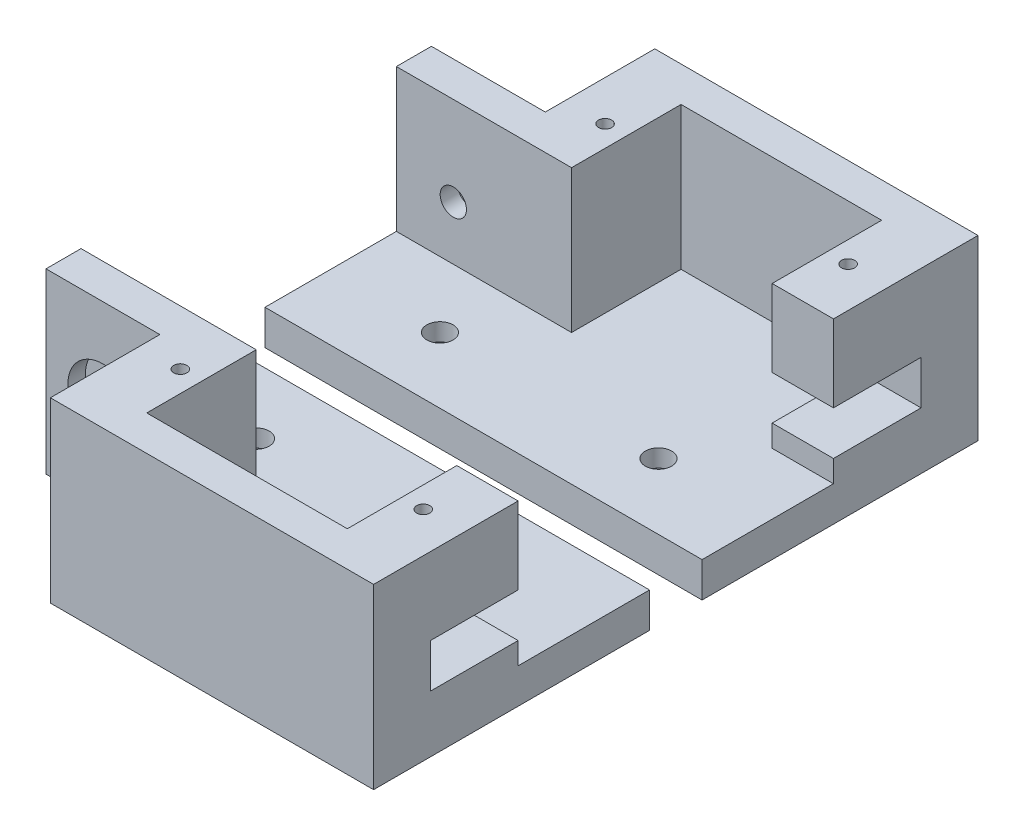
SolidWorks part; units mm, degrees
ref_plane "Front Plane" through (0, 0, 0) normal (0, 0, 1) x (1, 0, 0)
ref_plane "Top Plane" through (0, 0, 0) normal (0, 1, 0) x (1, 0, 0)
ref_plane "Right Plane" through (0, 0, 0) normal (1, 0, 0) x (0, 0, -1)
sketch "Sketch1" plane through (0, 0, 0) normal (0, 1, 0) x (1, 0, 0)
  line L0 (-20, 0) -> (0, 0)
  line L1 (0, 0) -> (0, 12.5)
  line L2 (0, 12.5) -> (22.9, 12.5)
  line L3 (22.9, 12.5) -> (22.9, 0)
  dimension "D1" = 22.9
  dimension "D2" = 12.5
  dimension "D3" = 20
extrude "Extrude-Thin1" add sketch "Sketch1" along normal blind 16.3 thin thin type one direction reverse wall 4
sketch "Sketch2" plane through (0, 0, 0) normal (0, -1, 0) x (1, 0, 0)
  line L2 (-20, 0) -> (-20, 15)
  line L3 (-20, 15) -> (26.9, 15)
  line L4 (26.9, 0) -> (26.9, 15)
  line L10 (22.9, 0) -> (22.9, -12.5)
  line L11 (22.9, -12.5) -> (0, -12.5)
  line L12 (0, -12.5) -> (0, 0)
  line L13 (0, 0) -> (-20, 0)
  line L14 (-20, 0) -> (-20, -4)
  line L15 (-20, -4) -> (-4, -4)
  line L16 (-4, -4) -> (-4, -16.5)
  line L17 (-4, -16.5) -> (26.9, -16.5)
  line L18 (26.9, -16.5) -> (26.9, 0)
  line L19 (26.9, 0) -> (22.9, 0)
  line L24 (-20, 0) -> (-20, -4)
  line L25 (-20, -4) -> (-4, -4)
  line L26 (-4, -4) -> (-4, -16.5)
  line L27 (-4, -16.5) -> (26.9, -16.5)
  line L28 (26.9, -16.5) -> (26.9, 0)
  dimension "D2" = 15
  dimension "D1" = 0
extrude "Boss-Extrude1" add sketch "Sketch2" along normal blind 4
sketch "Sketch3" plane through (0, 16.3, 0) normal (0, 1, 0) x (1, 0, 0)
  line L0 (-20, 4) -> (-4, 4) construction
  line L1 (-4, 16.5) -> (-7, 16.5)
  line L2 (-4, 16.5) -> (-4, 4)
  line L3 (-4, 4) -> (-7, 4)
  line L4 (-7, 16.5) -> (-7, 4)
  line L6 (26.9, 0) -> (29.9, 0)
  line L7 (26.9, 0) -> (26.9, 16.5)
  line L8 (26.9, 16.5) -> (29.9, 16.5)
  line L9 (29.9, 0) -> (29.9, 16.5)
  dimension "D1" = 3
  dimension "D2" = 3
extrude "Boss-Extrude2" add sketch "Sketch3" against normal up to surface (20.3 mm away) up to face at (0.9667, -4, -1.8333)
sketch "Sketch4" plane through (0, -4, 0) normal (0, -1, 0) x (1, 0, 0)
  line L1 (26.9, 15) -> (29.9, 15)
  line L2 (26.9, 15) -> (26.9, 0)
  line L3 (26.9, 0) -> (29.9, 0)
  line L4 (29.9, 15) -> (29.9, 0)
extrude "Boss-Extrude3" add sketch "Sketch4" against normal up to surface (4 mm away) up to face at (7.45, 0, 0.625)
sketch "Sketch6" plane through (0, 0, 0) normal (0, 1, 0) x (1, 0, 0)
  line L0 (-20, -7.5) -> (29.9, -7.5) construction
  line L1 (-20, -15) -> (-20, 0) construction
  line L2 (29.9, 0) -> (29.9, -15) construction
  circle A0 centre (-7.525, -7.5) radius 1.5
  circle A1 centre (17.425, -7.5) radius 1.5
  dimension "D1" = 3
  dimension "D2" = 3
  dimension "D3" = 49.9
  dimension "D4" = 24.95
  dimension "D5" = 12.475
extrude "Cut-Extrude1" cut sketch "Sketch6" against normal through all
sketch "Sketch7" plane through (0, -4, 0) normal (0, -1, 0) x (1, 0, 0)
  circle A0 centre (-7.525, 7.5) radius 4
  circle A1 centre (17.425, 7.5) radius 4
  dimension "D1" = 8
  dimension "D2" = 8
extrude "Cut-Extrude2" cut sketch "Sketch7" against normal blind 2
sketch "Sketch8" plane through (0, 0, -4) normal (0, 0, -1) x (-1, 0, 0)
  line L0 (13.5, 16.3) -> (13.5, -4) construction
  line L1 (20, 16.3) -> (7, 16.3) construction
  line L2 (20, -4) -> (7, -4) construction
  circle A0 centre (13.5, 6.15) radius 1.5
  dimension "D1" = 3
extrude "Cut-Extrude3" cut sketch "Sketch8" against normal through all
sketch "Sketch9" plane through (0, 0, -4) normal (0, 0, -1) x (-1, 0, 0)
  circle A0 centre (13.5, 6.15) radius 4
  dimension "D1" = 8
extrude "Cut-Extrude4" cut sketch "Sketch9" against normal blind 2
sketch "Sketch10" plane through (0, 16.3, 0) normal (0, 1, 0) x (1, 0, 0)
  line L0 (0, 0) -> (0, 12.5) construction
  line L1 (0, 6.25) -> (29.9, 6.25) construction
  line L2 (0, 0) -> (0, 12.5) construction
  line L3 (29.9, 0) -> (29.9, 16.5) construction
  line L4 (22.9, 12.5) -> (22.9, 0) construction
  circle A0 centre (-2.42, 6.25) radius 0.75
  circle A1 centre (25.32, 6.25) radius 0.75
  dimension "D2" = 1.5
  dimension "D3" = 1.5
  dimension "D1" = 2.42
  dimension "D4" = 2.42
extrude "Cut-Extrude5" cut sketch "Sketch10" against normal blind 10
sketch "Sketch11" plane through (0, 0, 0) normal (0, 0, 1) x (1, 0, 0)
  line L0 (22.9, 16.3) -> (22.9, 0) construction
  line L1 (22.9, 2.5) -> (29.9, 2.5)
  line L2 (22.9, 2.5) -> (22.9, 7.5)
  line L3 (22.9, 7.5) -> (29.9, 7.5)
  line L4 (29.9, 2.5) -> (29.9, 7.5)
  line L5 (29.9, 0) -> (29.9, 16.3) construction
  line L6 (29.9, 0) -> (22.9, 0) construction
  point P8 (29.9, 5)
  dimension "D1" = 5
  dimension "D2" = 5
extrude "Cut-Extrude6" cut sketch "Sketch11" against normal blind 10
ref_plane "Plane1" through (0, 0, 18) normal (0, 0, 1) x (1, 0, 0)
mirror "Mirror2" about plane through (0, 0, 18) normal (0, 0, 1) of bodies 110
equation "\"D4@Sketch6\"=\"D3@Sketch6\"/2"
equation "\"D5@Sketch6\"=\"D4@Sketch6\"/2"
equation "\"D4@Sketch10\"=\"D1@Sketch10\""
equation "\"D1@Sketch10\"=4.54/2 +0.15"
